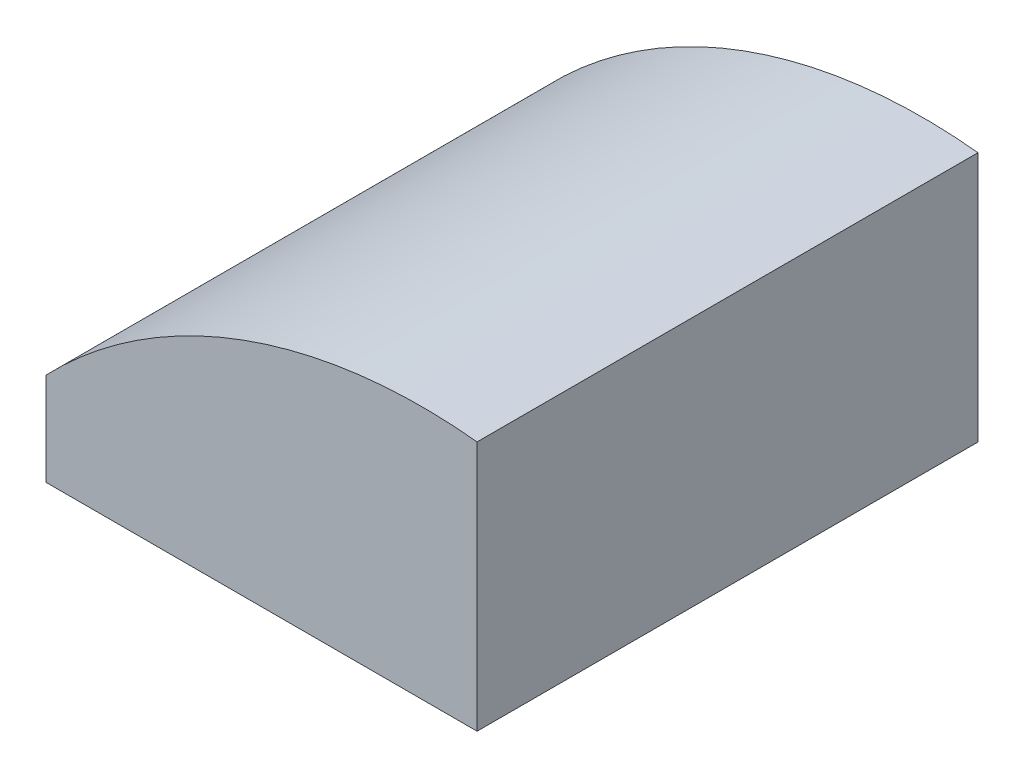
SolidWorks part; units mm, degrees
ref_plane "Front Plane" through (0, 0, 0) normal (0, 0, 1) x (1, 0, 0)
ref_plane "Top Plane" through (0, 0, 0) normal (0, 1, 0) x (1, 0, 0)
ref_plane "Right Plane" through (0, 0, 0) normal (1, 0, 0) x (0, 0, -1)
sketch "Sketch1" plane through (0, 0, 0) normal (0, 0, 1) x (1, 0, 0)
  line L0 (0, 0) -> (0, 9.4202)
  line L1 (43.7182, 25.4137) -> (43.7182, 0)
  line L3 (43.7182, 0) -> (0, 0)
  arc A0 (0, 9.4202) -> (43.7182, 25.4137) centre (38.1425, -27.0936) cw
extrude "Extrude1" add sketch "Sketch1" against normal blind 50.8
